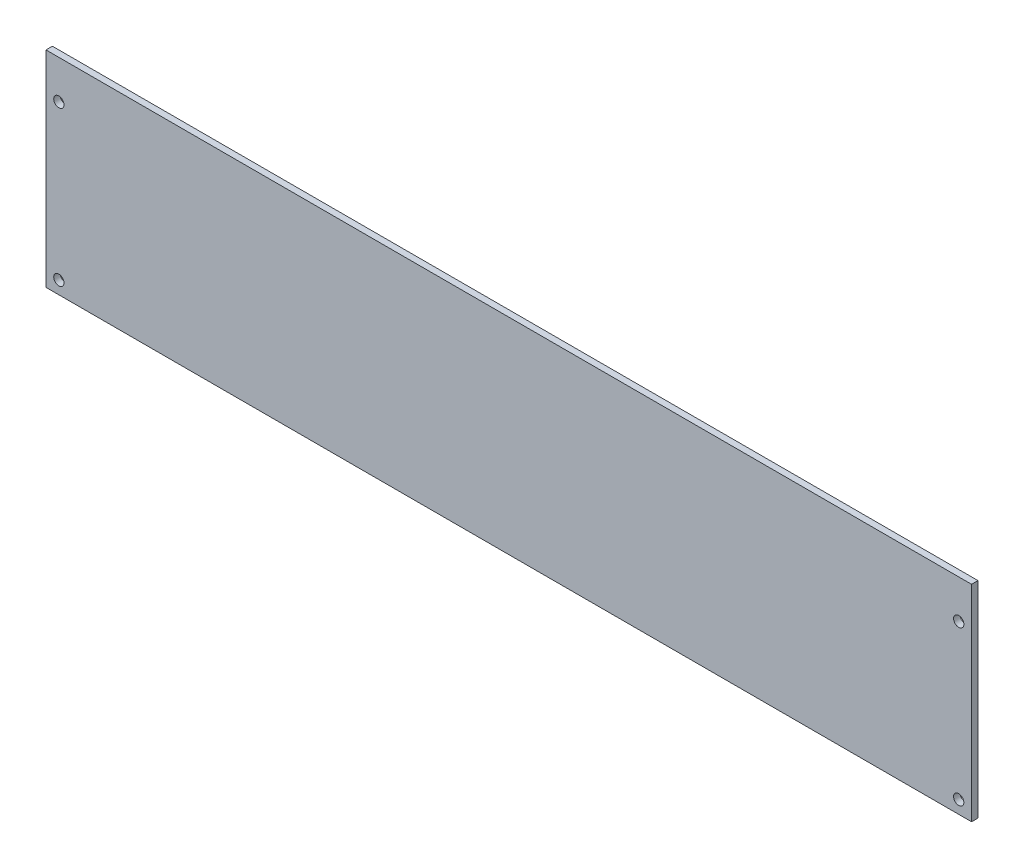
SolidWorks part; units mm, degrees
ref_plane "Front Plane" through (0, 0, 0) normal (0, 0, 1) x (1, 0, 0)
ref_plane "Top Plane" through (0, 0, 0) normal (0, 1, 0) x (1, 0, 0)
ref_plane "Right Plane" through (0, 0, 0) normal (1, 0, 0) x (0, 0, -1)
sketch "Sketch1" plane through (0, 0, 0) normal (0, 0, 1) x (1, 0, 0)
  line L1 (-381.527, 85.3319) -> (75.673, 85.3319)
  line L2 (-381.527, 85.3319) -> (-381.527, -16.2681)
  line L3 (-381.527, -16.2681) -> (75.673, -16.2681)
  line L4 (75.673, 85.3319) -> (75.673, -16.2681)
  circle A0 centre (-375.177, 66.2819) radius 2.54
  circle A1 centre (-375.177, -9.9181) radius 2.54
  circle A2 centre (69.323, 66.2819) radius 2.54
  circle A3 centre (69.323, -9.9181) radius 2.54
  dimension "D3" = 5.08
  dimension "D4" = 6.35
  dimension "D5" = 5.08
  dimension "D6" = 5.08
  dimension "D14" = 5.08
  dimension "D1" = 101.6
  dimension "D2" = 457.2
  dimension "D7" = 6.35
  dimension "D8" = 19.05
  dimension "D9" = 6.35
  dimension "D10" = 6.35
  dimension "D11" = 6.35
  dimension "D12" = 6.35
  dimension "D13" = 19.05
extrude "Boss-Extrude1" add sketch "Sketch1" against normal blind 3.175
